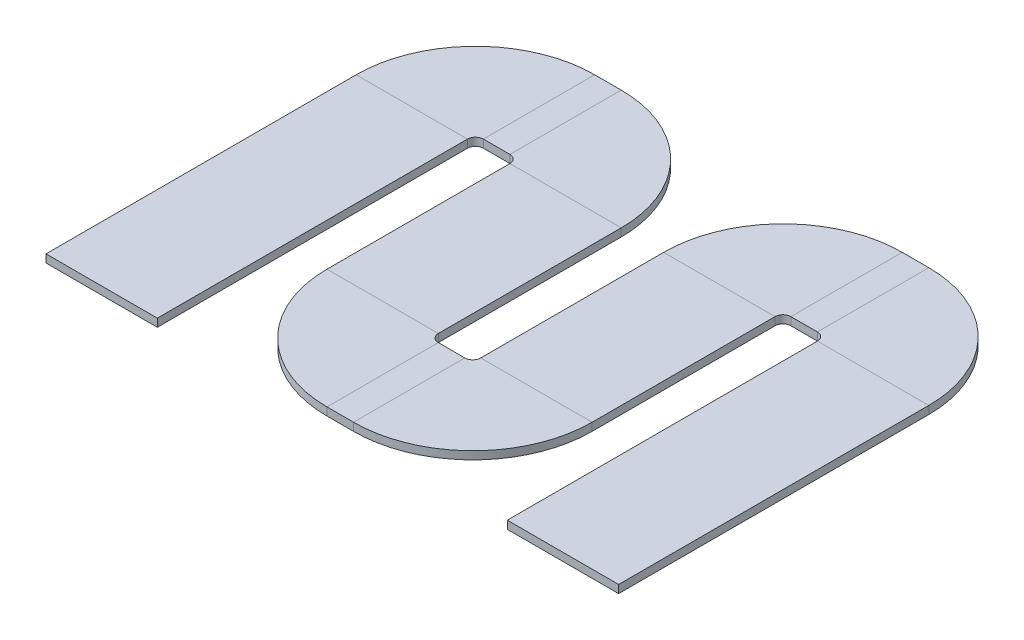
SolidWorks part; units mm, degrees
ref_plane "Front Plane" through (0, 0, 0) normal (0, 0, 1) x (1, 0, 0)
ref_plane "Top Plane" through (0, 0, 0) normal (0, 1, 0) x (1, 0, 0)
ref_plane "Right Plane" through (0, 0, 0) normal (1, 0, 0) x (0, 0, -1)
sketch "Sketch6" [suppressed] plane through (0, 0, 0) normal (0, 0, 1) x (1, 0, 0)
  line L1 (22.225, -9.525) -> (-22.225, -9.525)
  line L2 (22.225, -9.525) -> (22.225, -12.7)
  line L3 (22.225, -12.7) -> (-22.225, -12.7)
  line L4 (-22.225, -9.525) -> (-22.225, -12.7)
  line L5 (22.225, -9.525) -> (-22.225, -12.7) construction
  line L6 (22.225, -12.7) -> (-22.225, -9.525) construction
  point P0 (0, -11.1125)
  dimension "D1" = 44.45
  dimension "D2" = 3.175
  dimension "D3" = 12.7
sketch "Sketch1" plane through (0, 0, 0) normal (0, 1, 0) x (1, 0, 0)
  line L0 (0, 0) -> (0, 123.825)
  line L1 (25.4, 149.225) -> (35.9918, 149.225)
  line L2 (61.3918, 123.825) -> (61.3918, 50.8)
  line L3 (86.7918, 25.4) -> (97.3836, 25.4)
  line L4 (122.7836, 50.8) -> (122.7836, 123.825)
  line L5 (148.1836, 149.225) -> (158.7754, 149.225)
  line L6 (184.1754, 123.825) -> (184.1754, 0)
  arc A0 (86.7918, 25.4) -> (61.3918, 50.8) centre (86.7918, 50.8) cw
  arc A1 (61.3918, 123.825) -> (35.9918, 149.225) centre (35.9918, 123.825) ccw
  arc A2 (25.4, 149.225) -> (0, 123.825) centre (25.4, 123.825) ccw
  arc A3 (184.1754, 123.825) -> (158.7754, 149.225) centre (158.7754, 123.825) ccw
  arc A4 (148.1836, 149.225) -> (122.7836, 123.825) centre (148.1836, 123.825) ccw
  arc A5 (122.7836, 50.8) -> (97.3836, 25.4) centre (97.3836, 50.8) cw
  point P12 (0, 149.225)
  dimension "D2" = 25.4
  dimension "D3" = 61.3918
  dimension "D4" = 25.4
  dimension "D1" = 149.225
sweep "Sweep1" add profiles "Sketch6" path "Sketch1"
